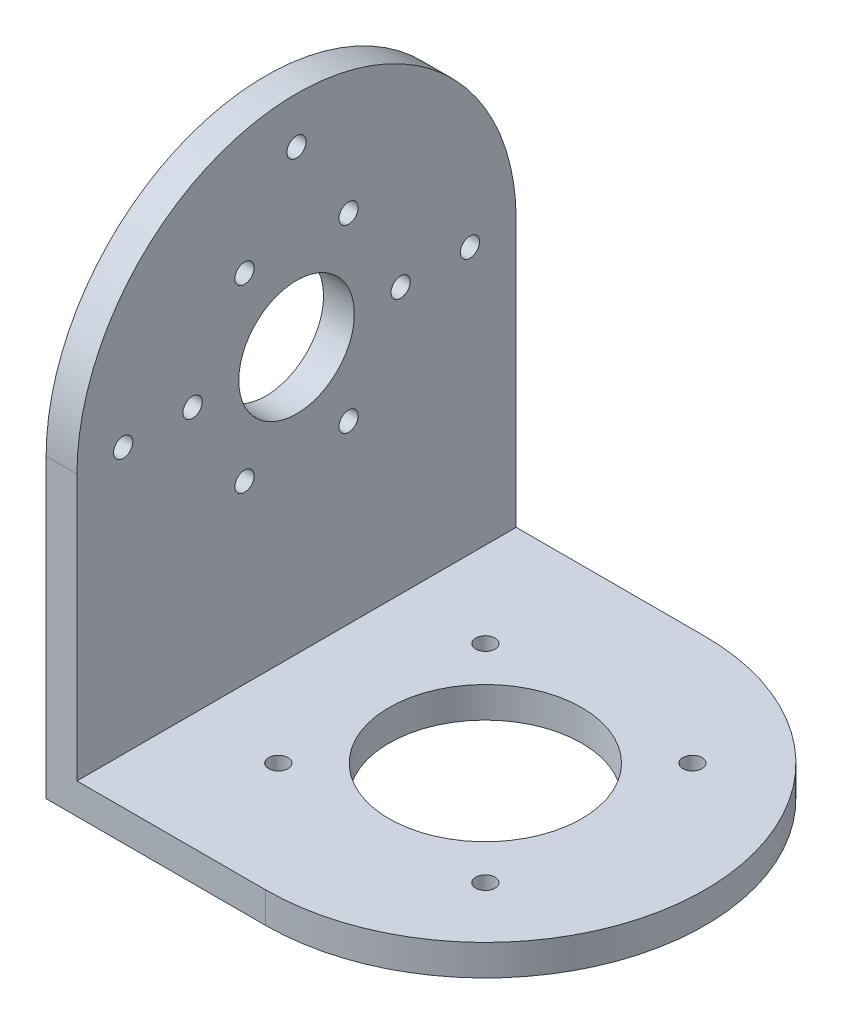
SolidWorks part; units mm, degrees
material "AISI 304"
ref_plane "前视基准面" through (0, 0, 0) normal (0, 0, 1) x (1, 0, 0)
ref_plane "上视基准面" through (0, 0, 0) normal (0, 1, 0) x (1, 0, 0)
ref_plane "右视基准面" through (0, 0, 0) normal (1, 0, 0) x (0, 0, -1)
other "Configuration Table"
sketch "草图1" plane through (0, 0, 0) normal (0, 0, 1) x (1, 0, 0)
  line L0 (0, 67) -> (0, 0)
  line L1 (0, 0) -> (57, 0)
  line L2 (57, 0) -> (57, 4)
  line L3 (57, 4) -> (4, 4)
  line L4 (4, 4) -> (4, 67)
  line L5 (4, 67) -> (0, 67)
  dimension "D1" = 67
  dimension "D2" = 57
  dimension "D3" = 4
  dimension "D4" = 4
extrude "凸台-拉伸1" add sketch "草图1" along normal blind 57
sketch "草图3" plane through (0, 0, 0) normal (0, -1, 0) x (1, 0, 0)
  line L0 (0, 57) -> (57, 57) construction
  line L1 (57, 57) -> (57, 0) construction
  line L2 (0, 0) -> (57, 0) construction
  line L3 (0, 0) -> (57, 0)
  line L4 (57, 57) -> (57, 0)
  line L5 (0, 57) -> (57, 57)
  circle A0 centre (28.5, 28.5) radius 28.5
  line M3 (57, 0) -> (57, 57)
  line M4 (57, 57) -> (0, 57)
  dimension "D1" = 57
extrude "切除-拉伸1" cut sketch "草图3" against normal blind 57 contours A0 L4 M4 | A0 L3 M3
sketch "草图4" plane through (0, 0, 0) normal (-1, 0, 0) x (0, 0, 1)
  line L0 (0, 67) -> (0, 0) construction
  line L1 (57, 67) -> (0, 67) construction
  line L2 (57, 67) -> (57, 0) construction
  line L3 (0, 67) -> (0, 0)
  line L4 (57, 67) -> (0, 67)
  line L5 (57, 67) -> (57, 0)
  circle A0 centre (28.5, 38.5) radius 28.5
  line M2 (0, 67) -> (0, 0)
  line M5 (57, 67) -> (0, 67)
  dimension "D1" = 57
extrude "切除-拉伸2" cut sketch "草图4" against normal blind 57 contours A0 L5 M5 | A0 L4 M2
sketch "草图5" plane through (0, 0, 0) normal (-1, 0, 0) x (0, 0, 1)
  line L0 (0, 38.5) -> (57, 38.5) construction
  line L1 (28.5, 67) -> (28.5, 0) construction
  line L2 (57, 0) -> (0, 0) construction
  arc A0 (57, 38.5) -> (0, 38.5) centre (28.5, 38.5) ccw construction
  circle A1 centre (28.5, 38.5) radius 7.5
  circle A2 centre (42, 38.5) radius 1.25
  dimension "D1" = 15
  dimension "D2" = 2.5
  dimension "D3" = 13.5
extrude "切除-拉伸3" cut sketch "草图5" against normal blind 57
pattern_circular "阵列(圆周)1" count 6 over 360 about axis through (0, 38.5, 28.5) along (1, 0, 0) of "切除-拉伸3"
sketch "草图6" plane through (0, 0, 0) normal (0, -1, 0) x (1, 0, 0)
  line L0 (0, 28.5) -> (57, 28.5) construction
  line L1 (0, 57) -> (0, 0) construction
  line L2 (28.5, 57) -> (28.5, 0) construction
  line L3 (28.5, 28.5) -> (70.8033, 70.8033) construction
  arc A0 (28.5, 0) -> (28.5, 57) centre (28.5, 28.5) ccw construction
  circle A1 centre (28.5, 28.5) radius 12.5
  circle A2 centre (41.935, 41.935) radius 1.25
  dimension "D1" = 25
  dimension "D3" = 2.5
  dimension "D2" = 45
  dimension "D4" = 19
extrude "切除-拉伸4" cut sketch "草图6" against normal blind 57
pattern_circular "阵列(圆周)2" count 4 over 360 about axis through (28.5, 0, 28.5) along (0, 1, 0) of "切除-拉伸4"
sketch "草图7" plane through (0, 0, 0) normal (-1, 0, 0) x (0, 0, 1)
  line L0 (0, 38.5) -> (57, 38.5) construction
  line L1 (28.5, 67) -> (28.5, 7.8511) construction
  arc A0 (57, 38.5) -> (0, 38.5) centre (28.5, 38.5) ccw construction
  circle A1 centre (51, 38.5) radius 1.25
  dimension "D1" = 2.5
  dimension "D2" = 22.5
extrude "切除-拉伸5" cut sketch "草图7" against normal blind 10
pattern_circular "阵列(圆周)3" count 3 over 180 about axis through (0, 38.5, 28.5) along (1, 0, 0) of "切除-拉伸5"
